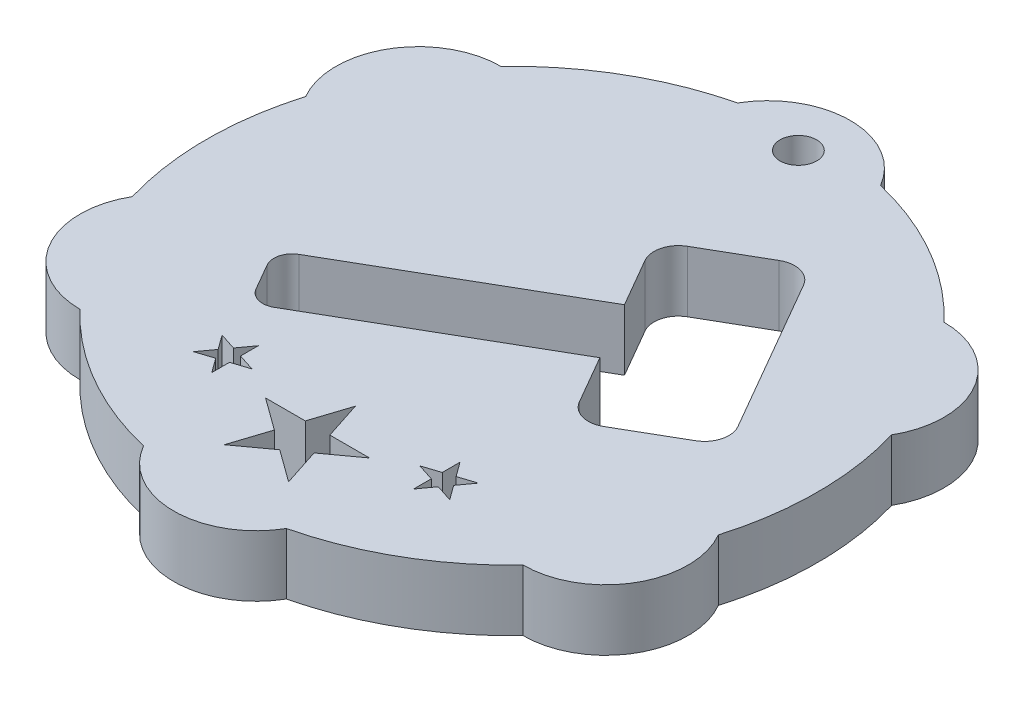
SolidWorks part; units mm, degrees
ref_plane "Front Plane" through (0, 0, 0) normal (0, 0, 1) x (1, 0, 0)
ref_plane "Top Plane" through (0, 0, 0) normal (0, 1, 0) x (1, 0, 0)
ref_plane "Right Plane" through (0, 0, 0) normal (1, 0, 0) x (0, 0, -1)
sketch "Sketch1" plane through (0, 0, 0) normal (0, 1, 0) x (1, 0, 0)
  line L0 (0, 0) -> (0, 41.8639) construction
  line L1 (-11.6913, 48.6139) -> (0, 41.8639) construction
  line L2 (0, 41.8639) -> (11.6913, 48.6139) construction
  line L3 (36.2552, 20.932) -> (47.9466, 14.182) construction
  line L4 (36.2552, 34.432) -> (36.2552, 20.932) construction
  line L5 (0, 0) -> (36.2552, 20.932) construction
  line L6 (36.2552, -20.932) -> (36.2552, -34.432) construction
  line L7 (47.9466, -14.182) -> (36.2552, -20.932) construction
  line L8 (0, 0) -> (36.2552, -20.932) construction
  line L9 (0, -41.8639) -> (-11.6913, -48.6139) construction
  line L10 (11.6913, -48.6139) -> (0, -41.8639) construction
  line L11 (0, 0) -> (0, -41.8639) construction
  line L12 (-36.2552, -20.932) -> (-47.9466, -14.182) construction
  line L13 (-36.2552, -34.432) -> (-36.2552, -20.932) construction
  line L14 (0, 0) -> (-36.2552, -20.932) construction
  line L15 (-36.2552, 20.932) -> (-36.2552, 34.432) construction
  line L16 (-47.9466, 14.182) -> (-36.2552, 20.932) construction
  line L17 (0, 0) -> (-36.2552, 20.932) construction
  line L18 (-27.2308, -12.8349) -> (-24.7308, -17.1651)
  line L19 (-20.6327, -18.2631) -> (13.1423, 1.2369)
  line L21 (7.6423, 10.7631) -> (-26.1327, -8.7369)
  line L23 (13.1423, 1.2369) -> (17.7423, -6.7306)
  line L25 (34.1968, 2.7694) -> (19.4968, 28.2306)
  line L26 (14.0327, 29.6947) -> (4.5064, 24.1947)
  line L27 (3.0423, 18.7306) -> (6.5064, 20.7306) construction
  line L28 (6.5064, 20.7306) -> (4.5064, 24.1947) construction
  line L29 (17.7423, -6.7306) -> (21.2064, -4.7306) construction
  line L30 (3.0423, 18.7306) -> (7.6423, 10.7631)
  line L31 (21.2064, -4.7306) -> (23.2064, -8.1947) construction
  line L32 (23.2064, -8.1947) -> (32.7327, -2.6947)
  line L33 (14.0327, 29.6947) -> (16.0327, 26.2306) construction
  line L34 (16.0327, 26.2306) -> (19.4968, 28.2306) construction
  line L35 (32.7327, -2.6947) -> (30.7327, 0.7694) construction
  line L36 (30.7327, 0.7694) -> (34.1968, 2.7694) construction
  line L37 (0, 41.8639) -> (0, 46.8639) construction
  line L38 (-26.1327, -8.7369) -> (-24.6327, -11.3349) construction
  line L39 (-24.6327, -11.3349) -> (-27.2308, -12.8349) construction
  line L40 (-24.7308, -17.1651) -> (-22.1327, -15.6651) construction
  line L41 (-22.1327, -15.6651) -> (-20.6327, -18.2631) construction
  line L42 (-2.0086, -31.8181) -> (0, -25.6363)
  line L43 (0, -25.6363) -> (2.0086, -31.8181)
  line L47 (2.0086, -31.8181) -> (8.5086, -31.8181)
  line L48 (8.5086, -31.8181) -> (3.25, -35.6387)
  line L51 (3.25, -35.6387) -> (5.2586, -41.8206)
  line L52 (5.2586, -41.8206) -> (0, -38)
  line L55 (0, -38) -> (-5.2586, -41.8206)
  line L56 (-5.2586, -41.8206) -> (-3.25, -35.6387)
  line L59 (-3.25, -35.6387) -> (-8.5086, -31.8181)
  line L60 (-8.5086, -31.8181) -> (-2.0086, -31.8181)
  line L69 (-2.0086, -31.8181) -> (2.0086, -31.8181) construction
  line L80 (-3.25, -35.6387) -> (17.7423, -28.8179) construction
  line L81 (13.7423, -28.8179) -> (16.5062, -27.9199)
  line L82 (16.5062, -27.9199) -> (16.5062, -25.0137)
  line L83 (16.5062, -25.0137) -> (18.2144, -27.3648)
  line L84 (18.2144, -27.3648) -> (20.9784, -26.4668)
  line L85 (20.9784, -26.4668) -> (19.2702, -28.8179)
  line L86 (19.2702, -28.8179) -> (20.9784, -31.1691)
  line L87 (20.9784, -31.1691) -> (18.2144, -30.271)
  line L88 (18.2144, -30.271) -> (16.5062, -32.6221)
  line L89 (16.5062, -32.6221) -> (16.5062, -29.716)
  line L90 (16.5062, -29.716) -> (13.7423, -28.8179)
  line L91 (17.7423, -28.8179) -> (16.5062, -25.0137) construction
  line L92 (-13.7423, -28.8179) -> (-16.5062, -27.9199)
  line L93 (-16.5062, -29.716) -> (-13.7423, -28.8179)
  line L94 (-16.5062, -32.6221) -> (-16.5062, -29.716)
  line L95 (-18.2144, -30.271) -> (-16.5062, -32.6221)
  line L96 (-20.9784, -31.1691) -> (-18.2144, -30.271)
  line L97 (-19.2702, -28.8179) -> (-20.9784, -31.1691)
  line L98 (-20.9784, -26.4668) -> (-19.2702, -28.8179)
  line L99 (-18.2144, -27.3648) -> (-20.9784, -26.4668)
  line L100 (-16.5062, -25.0137) -> (-18.2144, -27.3648)
  line L101 (-16.5062, -27.9199) -> (-16.5062, -25.0137)
  line L106 (0, 0) -> (8.2433, -4.7592) construction
  arc A0 (-11.6913, 48.6139) -> (-36.2552, 34.432) centre (0, 0) ccw
  arc A1 (-11.6913, 48.6139) -> (11.6913, 48.6139) centre (0, 41.8639) cw
  arc A2 (36.2552, 34.432) -> (47.9466, 14.182) centre (36.2552, 20.932) cw
  arc A3 (47.9466, -14.182) -> (36.2552, -34.432) centre (36.2552, -20.932) cw
  arc A4 (11.6913, -48.6139) -> (-11.6913, -48.6139) centre (0, -41.8639) cw
  arc A5 (-36.2552, -34.432) -> (-47.9466, -14.182) centre (-36.2552, -20.932) cw
  arc A6 (-47.9466, 14.182) -> (-36.2552, 34.432) centre (-36.2552, 20.932) cw
  arc A7 (36.2552, 34.432) -> (11.6913, 48.6139) centre (0, 0) ccw
  arc A8 (47.9466, -14.182) -> (47.9466, 14.182) centre (0, 0) ccw
  arc A9 (11.6913, -48.6139) -> (36.2552, -34.432) centre (0, 0) ccw
  arc A10 (-36.2552, -34.432) -> (-11.6913, -48.6139) centre (0, 0) ccw
  arc A11 (-47.9466, 14.182) -> (-47.9466, -14.182) centre (0, 0) ccw
  arc A13 (3.0423, 18.7306) -> (4.5064, 24.1947) centre (6.5064, 20.7306) cw
  arc A14 (17.7423, -6.7306) -> (23.2064, -8.1947) centre (21.2064, -4.7306) ccw
  arc A15 (14.0327, 29.6947) -> (19.4968, 28.2306) centre (16.0327, 26.2306) cw
  arc A16 (32.7327, -2.6947) -> (34.1968, 2.7694) centre (30.7327, 0.7694) ccw
  circle A17 centre (0, 46.8639) radius 3
  arc A18 (-24.7308, -17.1651) -> (-20.6327, -18.2631) centre (-22.1327, -15.6651) ccw
  arc A19 (-26.1327, -8.7369) -> (-27.2308, -12.8349) centre (-24.6327, -11.3349) ccw
  point P1 (-25.9808, -15)
  point P7 (0, -31.8181)
  point P69 (-7.8439, 12)
  point P70 (0, 0)
  dimension "D1" = 100
  dimension "D2" = 13.5
  dimension "D5" = 6
  dimension "D11" = 4
  dimension "D8" = 9.2
  dimension "D10" = 11
  dimension "D12" = 5
  dimension "D13" = 3
  dimension "D3" = 120
  dimension "D6" = 5
  dimension "D7" = 30
  dimension "D9" = 12
  dimension "D15" = 6.5
  dimension "D16" = 38
  dimension "D17" = 4
  dimension "D19" = 60
  dimension "D4" = 6
  dimension "D14" = 5
  dimension "D18" = 5
extrude "Boss-Extrude1" add sketch "Sketch1" along normal blind 10
